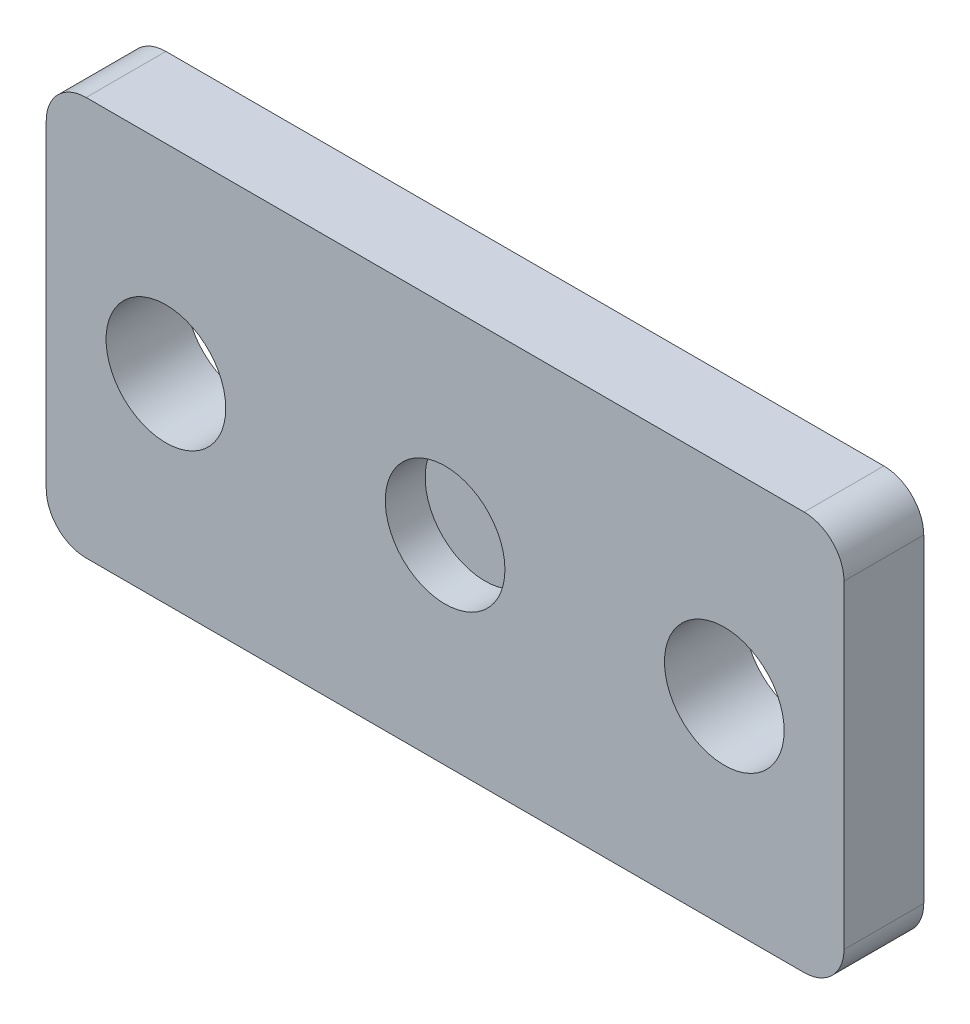
SolidWorks part; units mm, degrees
ref_plane "Front Plane" through (0, 0, 0) normal (0, 0, 1) x (1, 0, 0)
ref_plane "Top Plane" through (0, 0, 0) normal (0, 1, 0) x (1, 0, 0)
ref_plane "Right Plane" through (0, 0, 0) normal (1, 0, 0) x (0, 0, -1)
sketch "Sketch1" plane through (0, 0, 0) normal (0, 0, 1) x (1, 0, 0)
  line L1 (-5000, -2500) -> (5000, -2500)
  line L2 (-5000, -2500) -> (-5000, 2500)
  line L3 (-5000, 2500) -> (5000, 2500)
  line L4 (5000, -2500) -> (5000, 2500)
  line L5 (-5000, -2500) -> (5000, 2500) construction
  line L6 (-5000, 2500) -> (5000, -2500) construction
  point P0 (0, 0)
  dimension "D1" = 5000
  dimension "D2" = 2500
extrude "Boss-Extrude1" add sketch "Sketch1" along normal blind 1000
fillet "Fillet1" radius 500 1 edges at (-5000, 2500, 500)
fillet "Fillet2" radius 500 3 edges at (-5000, -2500, 500) (5000, -2500, 500) (5000, 2500, 500)
sketch "Sketch2" plane through (0, 0, 1000) normal (0, 0, 1) x (1, 0, 0)
  line L0 (4500, 2500) -> (-4500, 2500) construction
  circle A0 centre (-3500, 0) radius 750
  circle A1 centre (3500, 0) radius 750
  dimension "D3" = 1500
  dimension "D4" = 1500
  dimension "D1" = 3500
  dimension "D2" = 3500
  dimension "D5" = 2500
  dimension "D6" = 2500
extrude "Cut-Extrude1" cut sketch "Sketch2" against normal through all
sketch "Sketch3" plane through (0, 0, 1000) normal (0, 0, 1) x (1, 0, 0)
  circle A0 centre (0, 0) radius 750
  dimension "D1" = 1500
extrude "Cut-Extrude2" cut sketch "Sketch3" against normal blind 500
sketch "Sketch4" plane through (0, 0, 0) normal (0, 0, -1) x (-1, 0, 0)
  line L1 (-1000, -1000) -> (1000, -1000)
  line L2 (-1000, -1000) -> (-1000, 1000)
  line L3 (-1000, 1000) -> (1000, 1000)
  line L4 (1000, -1000) -> (1000, 1000)
  line L5 (-1000, -1000) -> (1000, 1000) construction
  line L6 (-1000, 1000) -> (1000, -1000) construction
  point P0 (0, 0)
  dimension "D1" = 1000
  dimension "D2" = 1000
extrude "Boss-Extrude2" add sketch "Sketch4" along normal blind 500
fillet "Fillet3" radius 250 7 edges at (1000, -1000, -250) (1000, 0, -500) (-1000, -1000, -250) (0, -1000, -500) (-1000, 0, -500) (0, 1000, -500) (1000, 1000, -250)
